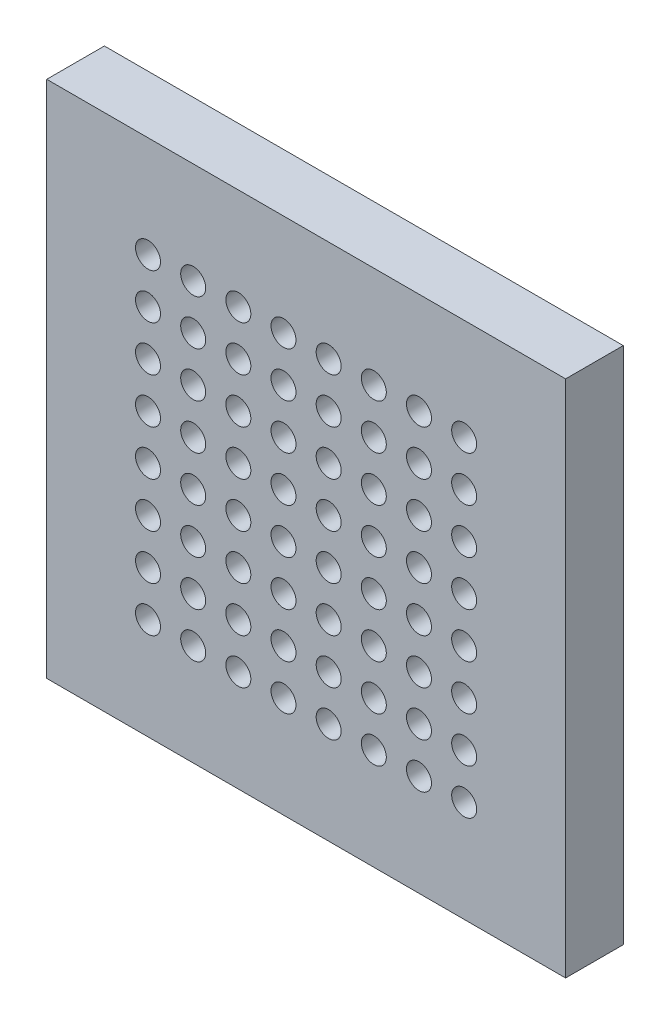
SolidWorks part; units mm, degrees
ref_plane "Front Plane" through (0, 0, 0) normal (0, 0, 1) x (1, 0, 0)
ref_plane "Top Plane" through (0, 0, 0) normal (0, 1, 0) x (1, 0, 0)
ref_plane "Right Plane" through (0, 0, 0) normal (1, 0, 0) x (0, 0, -1)
ref_plane "Plane1" through (0, 0, 43) normal (0, 0, 1) x (1, 0, 0)
sketch "Sketch2" plane through (0, 0, 43) normal (0, 0, 1) x (1, 0, 0)
  line L1 (-10, 10) -> (10, 10)
  line L2 (-10, 10) -> (-10, -10)
  line L3 (-10, -10) -> (10, -10)
  line L4 (10, 10) -> (10, -10)
  line L5 (-13.5, 13.5) -> (13.5, 13.5)
  line L6 (-13.5, 13.5) -> (-13.5, -13.5)
  line L7 (-13.5, -13.5) -> (13.5, -13.5)
  line L8 (13.5, 13.5) -> (13.5, -13.5)
  dimension "D1" = 20
  dimension "D2" = 20
  dimension "D3" = 27
  dimension "D4" = 27
  dimension "D5" = 10
  dimension "D6" = 10
  dimension "D7" = 13.5
  dimension "D8" = 13.5
sketch "Sketch5" plane through (0, 0, 43) normal (0, 0, 1) x (1, 0, 0)
  line L4 (-10, 10) -> (10, 10) construction
  line L5 (-10, 10) -> (-10, -10) construction
  line L6 (-10, -10) -> (10, -10) construction
  line L7 (10, 10) -> (10, -10) construction
  circle A0 centre (-8.23, 8.23) radius 0.65
  circle A1 centre (-5.88, 8.23) radius 0.65
  circle A2 centre (-3.53, 8.23) radius 0.65
  circle A3 centre (-1.18, 8.23) radius 0.65
  circle A4 centre (1.17, 8.23) radius 0.65
  circle A5 centre (3.52, 8.23) radius 0.65
  circle A6 centre (5.87, 8.23) radius 0.65
  circle A7 centre (8.22, 8.23) radius 0.65
  circle A8 centre (-5.88, 5.88) radius 0.65
  circle A9 centre (-3.53, 5.88) radius 0.65
  circle A10 centre (-1.18, 5.88) radius 0.65
  circle A11 centre (1.17, 5.88) radius 0.65
  circle A12 centre (3.52, 5.88) radius 0.65
  circle A13 centre (5.87, 5.88) radius 0.65
  circle A14 centre (8.22, 5.88) radius 0.65
  circle A15 centre (-5.88, 3.53) radius 0.65
  circle A16 centre (-3.53, 3.53) radius 0.65
  circle A17 centre (-1.18, 3.53) radius 0.65
  circle A18 centre (1.17, 3.53) radius 0.65
  circle A19 centre (3.52, 3.53) radius 0.65
  circle A20 centre (5.87, 3.53) radius 0.65
  circle A21 centre (8.22, 3.53) radius 0.65
  circle A22 centre (-5.88, 1.18) radius 0.65
  circle A23 centre (-3.53, 1.18) radius 0.65
  circle A24 centre (-1.18, 1.18) radius 0.65
  circle A25 centre (1.17, 1.18) radius 0.65
  circle A26 centre (3.52, 1.18) radius 0.65
  circle A27 centre (5.87, 1.18) radius 0.65
  circle A28 centre (8.22, 1.18) radius 0.65
  circle A29 centre (-5.88, -1.17) radius 0.65
  circle A30 centre (-3.53, -1.17) radius 0.65
  circle A31 centre (-1.18, -1.17) radius 0.65
  circle A32 centre (1.17, -1.17) radius 0.65
  circle A33 centre (3.52, -1.17) radius 0.65
  circle A34 centre (5.87, -1.17) radius 0.65
  circle A35 centre (8.22, -1.17) radius 0.65
  circle A36 centre (-5.88, -3.52) radius 0.65
  circle A37 centre (-3.53, -3.52) radius 0.65
  circle A38 centre (-1.18, -3.52) radius 0.65
  circle A39 centre (1.17, -3.52) radius 0.65
  circle A40 centre (3.52, -3.52) radius 0.65
  circle A41 centre (5.87, -3.52) radius 0.65
  circle A42 centre (8.22, -3.52) radius 0.65
  circle A43 centre (-5.88, -5.87) radius 0.65
  circle A44 centre (-3.53, -5.87) radius 0.65
  circle A45 centre (-1.18, -5.87) radius 0.65
  circle A46 centre (1.17, -5.87) radius 0.65
  circle A47 centre (3.52, -5.87) radius 0.65
  circle A48 centre (5.87, -5.87) radius 0.65
  circle A49 centre (8.22, -5.87) radius 0.65
  circle A50 centre (-5.88, -8.22) radius 0.65
  circle A51 centre (-3.53, -8.22) radius 0.65
  circle A52 centre (-1.18, -8.22) radius 0.65
  circle A53 centre (1.17, -8.22) radius 0.65
  circle A54 centre (3.52, -8.22) radius 0.65
  circle A55 centre (5.87, -8.22) radius 0.65
  circle A56 centre (8.22, -8.22) radius 0.65
  circle A57 centre (-8.23, 5.88) radius 0.65
  circle A58 centre (-8.23, 3.53) radius 0.65
  circle A59 centre (-8.23, 1.18) radius 0.65
  circle A60 centre (-8.23, -1.17) radius 0.65
  circle A61 centre (-8.23, -3.52) radius 0.65
  circle A62 centre (-8.23, -5.87) radius 0.65
  circle A63 centre (-8.23, -8.22) radius 0.65
  dimension "D1" = 8
  dimension "D3" = 1.3
  dimension "D4" = 2.35
  dimension "D5" = 1.77
  dimension "D6" = 1.77
  dimension "D8" = 2.35
  dimension "D2" = 8
extrude "Boss-Extrude2" add sketch "Sketch2" along normal blind 3 contours L5 L8 L7 L6
extrude "Cut-Extrude1" cut sketch "Sketch5" along normal blind 3
